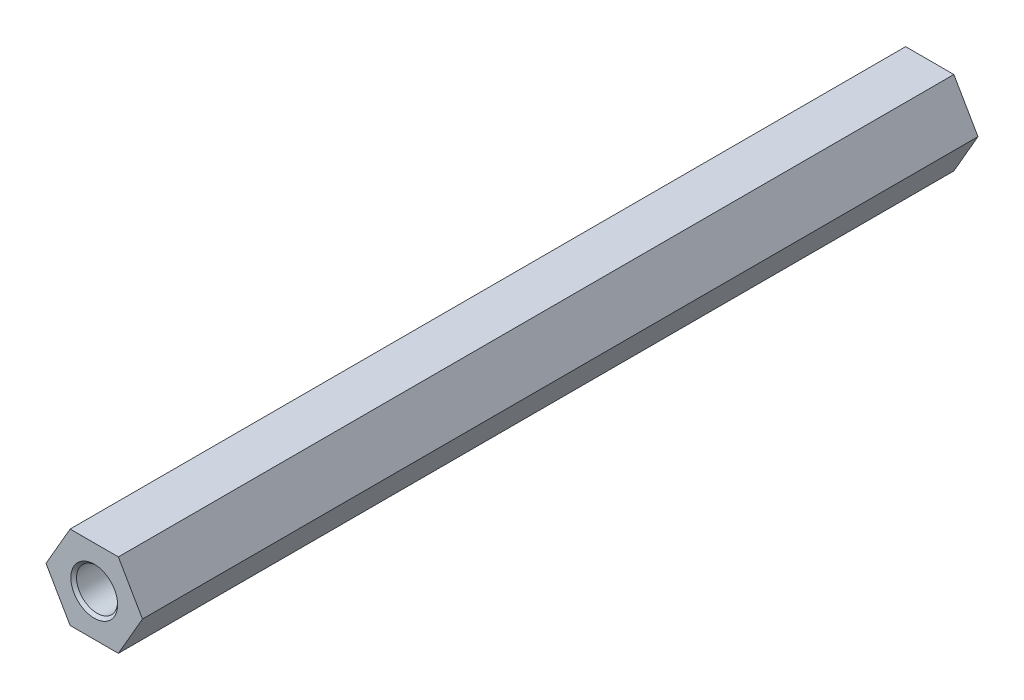
SolidWorks part; units mm, degrees
ref_plane "Front Plane" through (0, 0, 0) normal (0, 0, 1) x (1, 0, 0)
ref_plane "Top Plane" through (0, 0, 0) normal (0, 1, 0) x (1, 0, 0)
ref_plane "Right Plane" through (0, 0, 0) normal (1, 0, 0) x (0, 0, -1)
ref_plane "Plane1" through (0, 0, 25) normal (0, 0, 1) x (1, 0, 0)
sketch "Sketch1" plane through (0, 0, 25) normal (0, 0, 1) x (1, 0, 0)
  line L0 (-1.4434, -2.5) -> (1.4434, -2.5)
  line L1 (1.4434, -2.5) -> (2.8868, 0)
  line L2 (2.8868, 0) -> (1.4434, 2.5)
  line L3 (1.4434, 2.5) -> (-1.4434, 2.5)
  line L4 (-1.4434, 2.5) -> (-2.8868, 0)
  line L5 (-2.8868, 0) -> (-1.4434, -2.5)
extrude "Boss-Extrude1" add sketch "Sketch1" against normal blind 50
hole_wizard "M2 Clearance Hole1" positions "Sketch3" profile "Sketch2" hole size "M2" standard "ANSI Metric"
sketch "Sketch3" plane through (0, 0, -25) normal (0, 0, -1) x (-1, 0, 0)
  point P0 (0, 0)
sketch "Sketch2" plane through (0, 0, -25) normal (1, 0, 0) x (0, 1, 0)
  line L0 (0, 0) -> (0, 11.7388)
  line L1 (0, 11.7388) -> (1.2295, 11)
  line L2 (1.2295, 11) -> (1.2295, 0)
  line L5 (1.2295, 0) -> (0, 0)
  line L10 (0, 11.7388) -> (-1.2295, 11) construction
  line L11 (0, -6.35) -> (0, 107.95) construction
  dimension "Hole Dia." = 2.459
  dimension "Hole Depth" = 11
  dimension "Drill Angle" = 118
hole_wizard "M2 Clearance Hole2" positions "Sketch5" profile "Sketch4" hole size "M2" standard "ANSI Metric"
sketch "Sketch5" plane through (0, 0, 25) normal (0, 0, 1) x (1, 0, 0)
  point P0 (0, 0)
sketch "Sketch4" plane through (0, 0, 25) normal (1, 0, 0) x (0, -1, 0)
  line L0 (0, 0) -> (0, 11.7388)
  line L1 (0, 11.7388) -> (1.2295, 11)
  line L2 (1.2295, 11) -> (1.2295, 0)
  line L5 (1.2295, 0) -> (0, 0)
  line L10 (0, 11.7388) -> (-1.2295, 11) construction
  line L11 (0, -6.35) -> (0, 107.95) construction
  dimension "Hole Dia." = 2.459
  dimension "Hole Depth" = 11
  dimension "Drill Angle" = 118
chamfer "Chamfer1" distance 0.0002 angle 30 12 edges at (-2.1651, -1.25, 25) (-2.1651, 1.25, 25) (0, 2.5, 25) (2.1651, 1.25, 25) (2.1651, -1.25, 25) (0, -2.5, 25) (0, -2.5, -25) (2.1651, -1.25, -25) (2.1651, 1.25, -25) (0, 2.5, -25) (-2.1651, 1.25, -25) (-2.1651, -1.25, -25)
chamfer "Chamfer2" distance 0.1705 angle 45 2 edges at (-1.2295, 0, -25) (1.2295, 0, 25)
